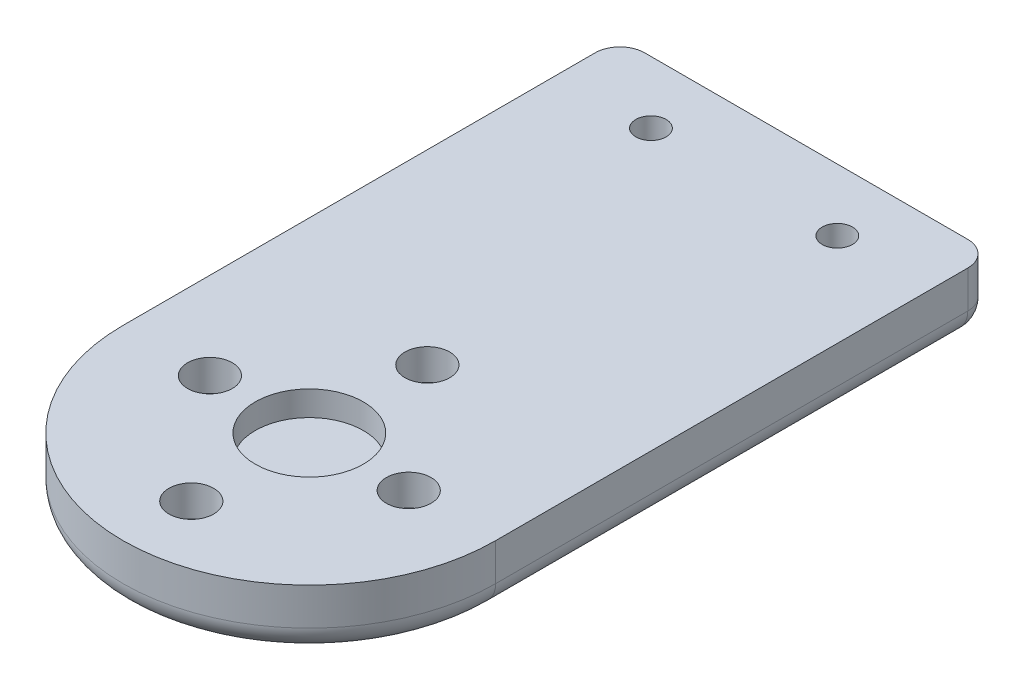
SolidWorks part; units mm, degrees
material "ABS"
ref_plane "Front" through (0, 0, 0) normal (0, 0, 1) x (1, 0, 0)
ref_plane "Top" through (0, 0, 0) normal (0, 1, 0) x (1, 0, 0)
ref_plane "Right" through (0, 0, 0) normal (1, 0, 0) x (0, 0, -1)
sketch "Sketch1" plane through (0, 0, 0) normal (0, 1, 0) x (1, 0, 0)
  line L0 (-15, 0) -> (-15, 40)
  line L1 (-15, 40) -> (15, 40)
  line L2 (15, 40) -> (15, 0)
  arc A0 (-15, 0) -> (15, 0) centre (0, 0) ccw
  dimension "D1" = 40
  dimension "D2" = 30
extrude "Boss-Extrude1" add sketch "Sketch1" along normal blind 5
sketch "Sketch2" plane through (0, 5, 0) normal (0, 1, 0) x (1, 0, 0)
  line L0 (-8, 0) -> (8, 0) construction
  line L1 (0, -9.5) -> (0, 9.5) construction
  circle A2 centre (-8, 0) radius 0.5
  circle A3 centre (0, 9.5) radius 0.5
  circle A4 centre (8, 0) radius 0.5
  circle A5 centre (0, -9.5) radius 0.5
  point P16 (0, 0)
  point P17 (0, 0)
  dimension "D4" = 1
  dimension "D1" = 19
  dimension "D3" = 16
extrude "Cut-Extrude1" cut sketch "Sketch2" against normal through all
hole_wizard "CBORE for #2 Binding Head Machine Screw1" positions "Sketch3" profile "Sketch5" counterbore size "#2" standard "ANSI Inch" end condition through all
sketch "Sketch3" plane through (0, 0, 0) normal (0, -1, 0) x (-1, 0, 0)
  line L0 (-7.5, 35) -> (7.5, 35) construction
  line L1 (0, 35) -> (0, 40) construction
  line L2 (-15, 40) -> (15, 40) construction
  point P0 (-7.5, 35)
  point P2 (7.5, 35)
  dimension "D1" = 5
  dimension "D2" = 15
sketch "Sketch5" plane through (7.5, 0, -35) normal (1, 0, 0) x (0, 0, -1)
  line L0 (0, 0) -> (0, 5)
  line L1 (0, 5) -> (1.2192, 5)
  line L3 (1.2192, 5) -> (1.2192, 2.5)
  line L4 (1.2192, 2.5) -> (2.7788, 2.5)
  line L5 (2.7788, 2.5) -> (2.7788, 0)
  line L7 (2.7788, 0) -> (0, 0)
  line L11 (0, -6.35) -> (0, 107.95) construction
  dimension "Thru Hole Dia." = 2.4384
  dimension "Thru Hole Depth" = 5
  dimension "C'Bore Dia." = 5.5575
  dimension "C'Bore Depth" = 2.5
fillet "Fillet1" radius 2 6 edges at (15, 0, -20) (0, 0, 15) (0, 0, -40) (-15, 0, -20) (15, 2.5, -40) (-15, 2.5, -40)
sketch "Sketch6" plane through (0, 5, 0) normal (0, 1, 0) x (1, 0, 0)
  circle A0 centre (0, 0) radius 4.35
  dimension "D1" = 8.7
extrude "Cut-Extrude2" cut sketch "Sketch6" against normal blind 2
hole_wizard "CBORE for M3 SBHCS1" positions "Sketch7" profile "Sketch9" counterbore size "M3" standard "ANSI Metric" end condition through all
sketch "Sketch7" plane through (0, 0, 0) normal (0, -1, 0) x (-1, 0, 0)
  point P0 (0, 9.5)
  point P3 (8, 0)
  point P6 (0, -9.5)
  point P9 (-8, 0)
sketch "Sketch9" plane through (0, 0, -9.5) normal (1, 0, 0) x (0, 0, -1)
  line L0 (0, 0) -> (0, 5)
  line L1 (0, 5) -> (1.8, 5)
  line L3 (1.8, 5) -> (1.8, 2.5)
  line L4 (1.8, 2.5) -> (3.35, 2.5)
  line L5 (3.35, 2.5) -> (3.35, 0)
  line L7 (3.35, 0) -> (0, 0)
  line L11 (0, -6.35) -> (0, 107.95) construction
  dimension "Thru Hole Dia." = 3.6
  dimension "Thru Hole Depth" = 5
  dimension "C'Bore Dia." = 6.7
  dimension "C'Bore Depth" = 2.5
